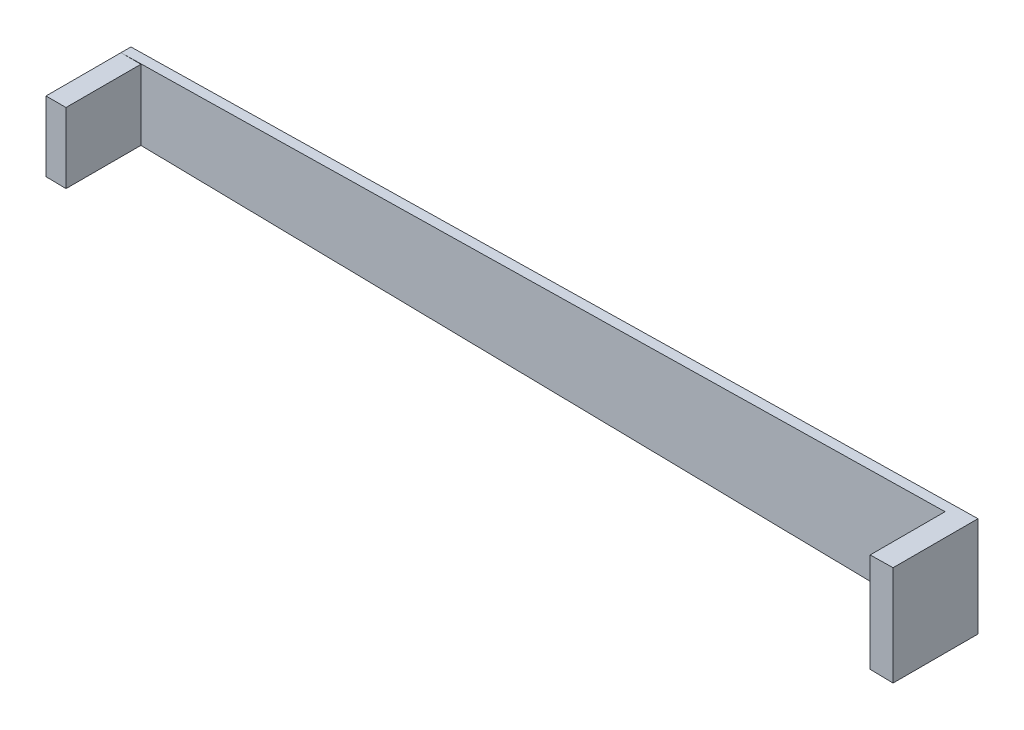
SolidWorks part; units mm, degrees
ref_plane "정면" through (0, 0, 0) normal (0, 0, 1) x (1, 0, 0)
ref_plane "윗면" through (0, 0, 0) normal (0, 1, 0) x (1, 0, 0)
ref_plane "우측면" through (0, 0, 0) normal (1, 0, 0) x (0, 0, -1)
sketch "스케치1" plane through (0, 0, 0) normal (0, 0, 1) x (1, 0, 0)
  line L1 (-69.825, -7) -> (99.75, -10)
  line L2 (-69.825, -7) -> (-69.825, 7)
  line L3 (-69.825, 7) -> (99.75, 10)
  line L4 (99.75, -10) -> (99.75, 10)
  line L5 (-69.825, -7) -> (99.75, 10) construction
  line L6 (-69.825, 7) -> (99.75, -10) construction
  point P0 (0, 0)
  dimension "D1" = 14
  dimension "D2" = 20
extrude "보스-돌출1" add sketch "스케치1" along normal blind 2
sketch "스케치2" plane through (0, 0, 2) normal (0, 0, 1) x (1, 0, 0)
  line L0 (-69.825, -7) -> (99.75, -10) construction
  line L1 (-69.825, 7) -> (-65.825, 7)
  line L2 (-69.825, 7) -> (-69.825, -7.0708)
  line L3 (-69.825, -7.0708) -> (-65.825, -7.0708)
  line L4 (-65.825, 7) -> (-65.825, -7.0708)
  line L6 (99.75, 10) -> (95.16, 10)
  line L7 (99.75, 10) -> (99.75, -9.9188)
  line L8 (99.75, -9.9188) -> (95.16, -9.9188)
  line L9 (95.16, 10) -> (95.16, -9.9188)
  line M1 (99.75, -10) -> (99.75, 10)
  line M2 (99.75, 10) -> (-69.825, 7)
  line M3 (-69.825, 7) -> (-69.825, -7)
  line M4 (-69.825, -7) -> (99.75, -10)
  dimension "D1" = 4
  dimension "D2" = 4.59
extrude "보스-돌출2" add sketch "스케치2" along normal blind 15 contours L4 L1 M3 M4 | L9 L8 M2 M1 | L8 M1 M4
